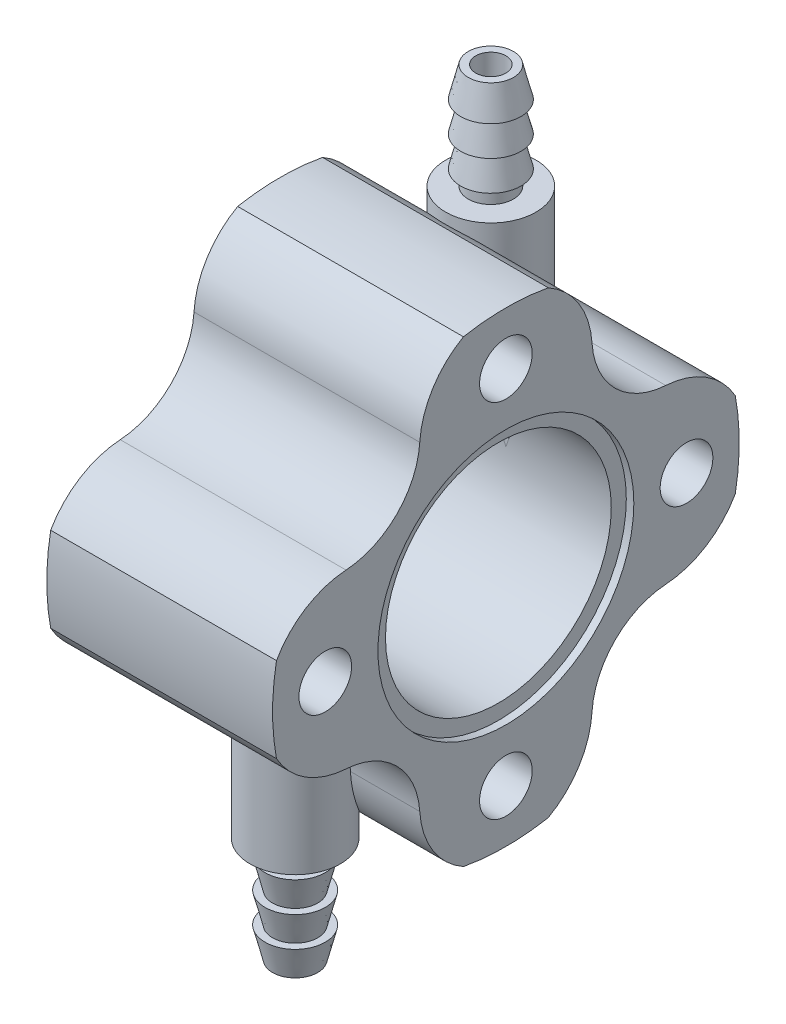
SolidWorks part; units mm, degrees
ref_plane "Front Plane" through (0, 0, 0) normal (0, 0, 1) x (1, 0, 0)
ref_plane "Top Plane" through (0, 0, 0) normal (0, 1, 0) x (1, 0, 0)
ref_plane "Right Plane" through (0, 0, 0) normal (1, 0, 0) x (0, 0, -1)
sketch "Sketch2" plane through (0, 0, 0) normal (1, 0, 0) x (0, 0, -1)
  line L0 (-12, 0) -> (-10.9602, 10.9602) construction
  line L1 (-10.9602, 10.9602) -> (0, 12) construction
  line L2 (0, 55) -> (0, -55) construction
  arc A0 (-15.2412, 2.8209) -> (-15.2412, -2.8209) centre (0, 0) ccw
  circle A1 centre (0, 12) radius 1.75
  circle A2 centre (12, 0) radius 1.75
  circle A3 centre (0, -12) radius 1.75
  circle A4 centre (-12, 0) radius 1.75
  circle A5 centre (0, 0) radius 7.5
  circle A6 centre (0, 0) radius 8.5 construction
  arc A7 (-10.6207, 5.7211) -> (-5.7211, 10.6207) centre (-10.9602, 10.9602) ccw
  circle A8 centre (0, 0) radius 10.25 construction
  arc A9 (-5.7211, 10.6207) -> (-2.8209, 15.2412) centre (0, 10.25) cw
  arc A10 (-2.8209, 15.2412) -> (-6.6728, 13.9901) centre (0, 0) ccw construction
  arc A11 (-5.7336, 11.456) -> (-6.6728, 13.9901) centre (-10.9602, 10.9602) ccw construction
  arc A12 (-6.6728, 13.9901) -> (-10.9602, 10.9602) centre (0, 0) ccw construction
  arc A13 (-10.9602, 10.9602) -> (-13.9901, 6.6728) centre (0, 0) ccw construction
  arc A14 (-5.7211, 10.6207) -> (-5.7336, 11.456) centre (-10.9602, 10.9602) ccw construction
  arc A15 (5.7211, 10.6207) -> (2.8209, 15.2412) centre (0, 10.25) ccw
  arc A16 (5.7211, 10.6207) -> (10.6207, 5.7211) centre (10.9602, 10.9602) ccw
  arc A17 (10.6207, 5.7211) -> (15.2412, 2.8209) centre (10.25, 0) cw
  arc A18 (10.6207, -5.7211) -> (15.2412, -2.8209) centre (10.25, 0) ccw
  arc A19 (10.6207, -5.7211) -> (5.7211, -10.6207) centre (10.9602, -10.9602) ccw
  arc A20 (5.7211, -10.6207) -> (2.8209, -15.2412) centre (0, -10.25) cw
  arc A21 (-5.7211, -10.6207) -> (-2.8209, -15.2412) centre (0, -10.25) ccw
  arc A22 (-5.7211, -10.6207) -> (-10.6207, -5.7211) centre (-10.9602, -10.9602) ccw
  arc A23 (-10.6207, -5.7211) -> (-15.2412, -2.8209) centre (-10.25, 0) cw
  arc A24 (-10.6207, 5.7211) -> (-15.2412, 2.8209) centre (-10.25, 0) ccw
  arc A25 (6.6728, 13.9901) -> (5.7211, 10.6207) centre (10.9602, 10.9602) ccw construction
  arc A26 (13.9901, -6.6728) -> (10.6207, -5.7211) centre (10.9602, -10.9602) ccw construction
  arc A27 (2.8209, -15.2412) -> (13.9901, -6.6728) centre (0, 0) ccw construction
  arc A28 (15.2412, -2.8209) -> (15.2412, 2.8209) centre (0, 0) ccw
  arc A29 (13.9901, -6.6728) -> (15.2412, -2.8209) centre (0, 0) ccw construction
  arc A30 (15.2412, 2.8209) -> (6.6728, 13.9901) centre (0, 0) ccw construction
  arc A31 (2.8209, 15.2412) -> (-2.8209, 15.2412) centre (0, 0) ccw
  arc A32 (-6.6728, -13.9901) -> (-2.8209, -15.2412) centre (0, 0) ccw construction
  arc A33 (-2.8209, -15.2412) -> (2.8209, -15.2412) centre (0, 0) ccw
  arc A34 (-6.6728, -13.9901) -> (-5.7211, -10.6207) centre (-10.9602, -10.9602) ccw construction
  arc A35 (-15.2412, -2.8209) -> (-6.6728, -13.9901) centre (0, 0) ccw construction
  arc A36 (-13.9901, 6.6728) -> (-11.456, 5.7336) centre (-10.9602, 10.9602) ccw construction
  arc A37 (-13.9901, 6.6728) -> (-15.2412, 2.8209) centre (0, 0) ccw construction
  arc A38 (6.6728, 13.9901) -> (2.8209, 15.2412) centre (0, 0) ccw construction
  arc A39 (-11.456, 5.7336) -> (-10.6207, 5.7211) centre (-10.9602, 10.9602) ccw construction
  point P14 (0, 0)
  point P49 (0, 0)
  dimension "D1" = 31
  dimension "D3" = 3.5
  dimension "D5" = 15
  dimension "D6" = 17
  dimension "D7" = 4
  dimension "D4" = 12
  dimension "D2" = 4
extrude "Flange" add sketch "Sketch2" along normal blind 15
sketch "Sketch3" plane through (15, 0, 0) normal (1, 0, 0) x (0, 0, -1)
  circle A0 centre (0, 0) radius 8.5
  dimension "D1" = 17
extrude "O-Ring Seat" cut sketch "Sketch3" against normal blind 0.5
ref_plane "MidPlane Reference" through (7.5, 0, 0) normal (-1, 0, 0) x (0, 0, 1)
mirror "Mirror1" about plane through (7.5, 0, 0) normal (-1, 0, 0) of "O-Ring Seat"
sketch "Sketch5" plane through (0, 0, 0) normal (0, 1, 0) x (1, 0, 0)
  line L0 (7.5, 15.4) -> (7.5, -15.4) construction
  circle A0 centre (7.5, 6.5) radius 1
  dimension "D1" = 2
  dimension "D2" = 6.5
extrude "Outlet" cut sketch "Sketch5" along normal through all
ref_plane "Plane2" through (0, 15.5, 0) normal (0, 1, 0) x (1, 0, 0)
sketch "Sketch6" plane through (0, 15.5, 0) normal (0, 1, 0) x (1, 0, 0)
  circle A2 centre (7.5, 6.5) radius 1
  circle A3 centre (7.5, 6.5) radius 3
  dimension "D1" = 2
extrude "Boss-Extrude2" add sketch "Sketch6" against normal up to next
sketch "Sketch8" plane through (7.5, 0, 0) normal (-1, 0, 0) x (0, 0, 1)
  line L0 (-8, 15.5) -> (-8, 16.5)
  line L1 (-8, 16.5) -> (-8.5, 16.5)
  line L2 (-8.5, 16.5) -> (-8, 18.5)
  line L3 (-8, 18.5) -> (-8.5, 18.5)
  line L4 (-8.5, 18.5) -> (-8, 20.5)
  line L5 (-8, 20.5) -> (-8.5, 20.5)
  line L6 (-8.5, 20.5) -> (-8, 22.5)
  line L7 (-8, 22.5) -> (-7.5, 22.5)
  line L8 (-7.5, 22.5) -> (-7.5, 15.5)
  line L9 (-7.5, 15.5) -> (-8, 15.5)
  line L10 (-3.5, 15.5) -> (-9.5, 15.5) construction
  line L11 (-5.5, 15.5) -> (-7.5, 15.5) construction
  point P14 (-6.5, 15.5)
  dimension "D1" = 1
  dimension "D2" = 0.5
  dimension "D3" = 0.5
  dimension "D4" = 2
  dimension "D5" = 1
ref_axis "Axis1" through (7.5, 15.5, -6.5) along (0, -1, 0)
revolve "Revolve1" add sketch "Sketch8" angle 360 about axis through (7.5, 15.5, -6.5) along (0, -1, 0)
pattern_circular "CirPattern1" count 2 every 180 about axis through (0.5, 0, 0) along (-1, 0, 0) of "Outlet", "Boss-Extrude2", "Revolve1"
